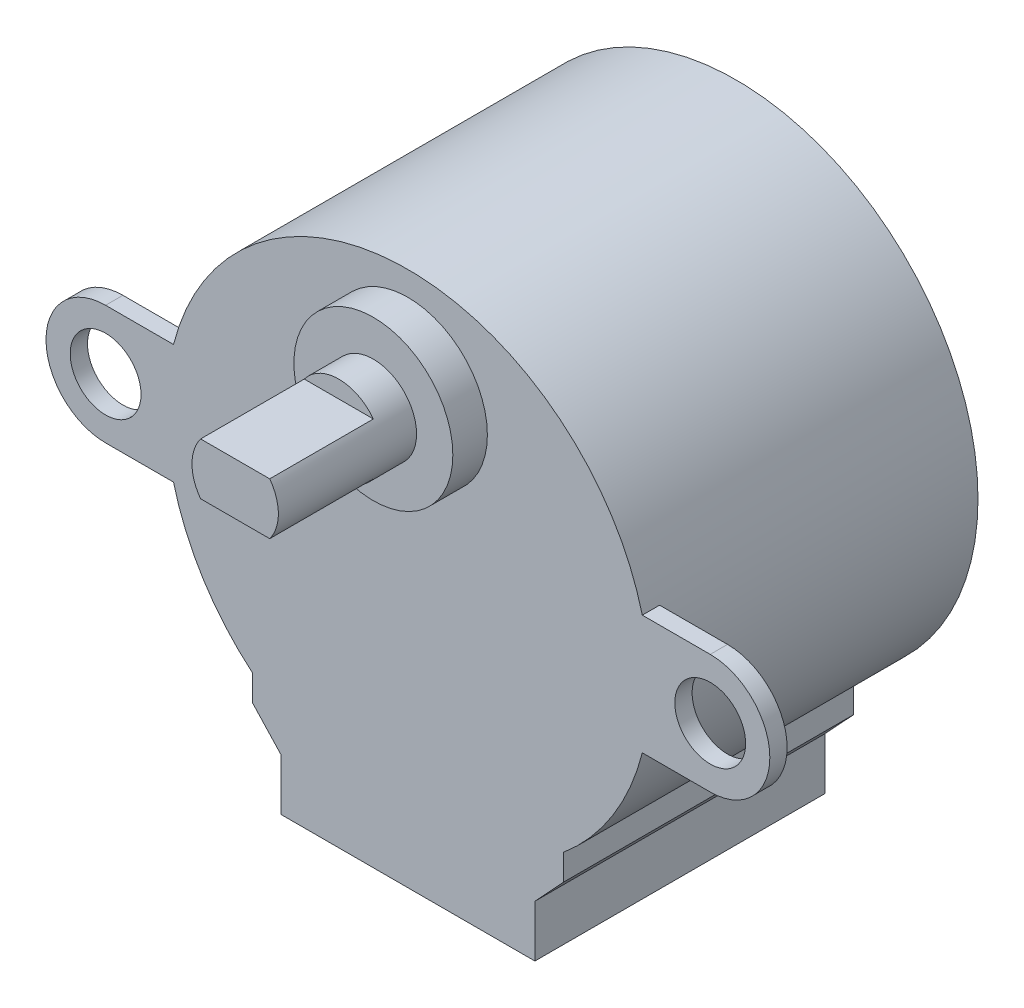
SolidWorks part; units mm, degrees
material "Air"
ref_plane "Front Plane" through (0, 0, 0) normal (0, 0, 1) x (1, 0, 0)
ref_plane "Top Plane" through (0, 0, 0) normal (0, 1, 0) x (1, 0, 0)
ref_plane "Right Plane" through (0, 0, 0) normal (1, 0, 0) x (0, 0, -1)
sketch "Sketch1" plane through (0, 0, 0) normal (0, 0, 1) x (1, 0, 0)
  circle A0 centre (0, 0) radius 14
  dimension "D1" = 28
extrude "Boss-Extrude1" add sketch "Sketch1" along normal blind 19
sketch "Sketch3" plane through (0, 0, 19) normal (0, 0, 1) x (1, 0, 0)
  line L0 (672.6511, 1264.4521) -> (697.6511, 1264.4521) construction
  line L1 (-576.9945, 40.9982) -> (-576.9945, 65.9982) construction
  dimension "D1" = 25
  dimension "D2" = 25
sketch "Sketch2" plane through (0, 0, 19) normal (0, 0, 1) x (1, 0, 0)
  line L0 (-7.35, -17) -> (7.35, -17)
  line L1 (7.35, -17) -> (7.35, -14)
  line L2 (7.35, -14) -> (9, -12.2238)
  line L3 (9, -12.2238) -> (9, -10.7238)
  line L4 (-7.35, -17) -> (-7.35, -14)
  line L5 (-7.35, -14) -> (-9, -12.2238)
  line L6 (-9, -12.2238) -> (-9, -10.7238)
  line L7 (9, -10.7238) -> (-9, -10.7238) construction
  circle A0 centre (0, 0) radius 14 construction
  arc A1 (-9, -10.7238) -> (9, -10.7238) centre (0, 0) ccw
  point P2 (0, -17)
  dimension "D1" = 14.7
  dimension "D2" = 17
  dimension "D3" = 18
  dimension "D4" = 3
  dimension "D5" = 3
  dimension "D6" = 1.5
  dimension "D7" = 1.5
extrude "Boss-Extrude2" add sketch "Sketch2" against normal blind 16.8 contours L1 L2 L3 A1 L6 L5 L4 L0
sketch "Sketch4" plane through (0, -17, 0) normal (0, -1, 0) x (1, 0, 0)
  line L0 (-3, 17.25) -> (3, 17.25) construction
  line L1 (-3, 17.75) -> (3, 17.75)
  line L2 (-3, 16.75) -> (3, 16.75)
  line L3 (-7.35, 19) -> (7.35, 19) construction
  arc A0 (-3, 17.75) -> (-3, 16.75) centre (-3, 17.25) ccw
  arc A1 (3, 16.75) -> (3, 17.75) centre (3, 17.25) ccw
  point P2 (0, 17.25)
  dimension "D1" = 6
  dimension "D2" = 0.5
  dimension "D3" = 1.75
extrude "Cut-Extrude1" cut sketch "Sketch4" against normal blind 2
sketch "Sketch5" plane through (0, 0, 19) normal (0, 0, 1) x (1, 0, 0)
  line L0 (0, 14) -> (0, -18.7354) construction
  line L1 (0, 0) -> (9.5563, 0) construction
  line L2 (-17.5, 3.45) -> (-13.5683, 3.45)
  line L3 (-17.5, -3.45) -> (-13.5683, -3.45)
  line L4 (17.5, -3.45) -> (13.5683, -3.45)
  line L5 (17.5, 3.45) -> (13.5683, 3.45)
  circle A0 centre (-17.5, 0) radius 2.05
  arc A3 (-17.5, 3.45) -> (-17.5, -3.45) centre (-17.5, 0) ccw
  arc A4 (9, -10.7238) -> (-9, -10.7238) centre (0, 0) ccw construction
  arc A5 (13.5683, 3.45) -> (13.5683, -3.45) centre (0, 0) cw
  arc A6 (-13.5683, 3.45) -> (-13.5683, -3.45) centre (0, 0) ccw
  arc A7 (17.5, 3.45) -> (17.5, -3.45) centre (17.5, 0) cw
  circle A8 centre (17.5, 0) radius 2.05
  dimension "D1" = 4.1
  dimension "D3" = 6.9
extrude "Boss-Extrude3" add sketch "Sketch5" against normal blind 1
sketch "Sketch6" plane through (0, 0, 19) normal (0, 0, 1) x (1, 0, 0)
  line L0 (-24.9917, 0) -> (30.299, 0) construction
  line L1 (0, 14.8773) -> (0, -18.0753) construction
  circle A0 centre (0, 8) radius 4.6
  dimension "D1" = 9.2
  dimension "D2" = 8
extrude "Boss-Extrude4" add sketch "Sketch6" along normal blind 2
sketch "Sketch7" plane through (0, 0, 21) normal (0, 0, 1) x (1, 0, 0)
  circle A0 centre (0, 8) radius 2.5
  dimension "D1" = 5
extrude "Boss-Extrude5" add sketch "Sketch7" along normal blind 8
sketch "Sketch8" plane through (0, 0, 29) normal (0, 0, 1) x (1, 0, 0)
  line L0 (-2, 9.5) -> (2, 9.5)
  line L1 (-2, 6.5) -> (2, 6.5)
  line L2 (0, 9.5) -> (0, 6.5) construction
  circle A0 centre (0, 8) radius 2.5
  point P9 (0, 8)
  circle M4 centre (0, 8) radius 2.5
  dimension "D2" = 5
  dimension "D1" = 3
extrude "Cut-Extrude2" cut sketch "Sketch8" against normal blind 6 contours L0 M4 | L1 M4
sketch "Sketch9" plane through (0, 0, 19) normal (0, 0, 1) x (1, 0, 0)
  line L11 (13.5683, -3.45) -> (17.5, -3.45)
  line L12 (17.5, 3.45) -> (13.5683, 3.45)
  line L13 (-13.5683, 3.45) -> (-17.5, 3.45)
  line L14 (-17.5, -3.45) -> (-13.5683, -3.45)
  line L15 (-9, -10.7238) -> (-9, -12.2238)
  line L16 (-9, -12.2238) -> (-7.35, -14)
  line L17 (-7.35, -14) -> (-7.35, -17)
  line L18 (-7.35, -17) -> (7.35, -17)
  line L19 (7.35, -17) -> (7.35, -14)
  line L20 (7.35, -14) -> (9, -12.2238)
  line L21 (9, -12.2238) -> (9, -10.7238)
  line L22 (13.5683, -3.45) -> (17.5, -3.45)
  line L23 (17.5, 3.45) -> (13.5683, 3.45)
  line L24 (-13.5683, 3.45) -> (-17.5, 3.45)
  line L25 (-17.5, -3.45) -> (-13.5683, -3.45)
  line L26 (-9, -10.7238) -> (-9, -12.2238)
  line L27 (-9, -12.2238) -> (-7.35, -14)
  line L28 (-7.35, -14) -> (-7.35, -17)
  line L29 (-7.35, -17) -> (7.35, -17)
  line L30 (7.35, -17) -> (7.35, -14)
  line L31 (7.35, -14) -> (9, -12.2238)
  line L32 (9, -12.2238) -> (9, -10.7238)
  arc A5 (9, -10.7238) -> (13.5683, -3.45) centre (0, 0) ccw
  arc A6 (17.5, -3.45) -> (17.5, 3.45) centre (17.5, 0) ccw
  arc A7 (13.5683, 3.45) -> (-13.5683, 3.45) centre (0, 0) ccw
  arc A8 (-17.5, 3.45) -> (-17.5, -3.45) centre (-17.5, 0) ccw
  arc A9 (-13.5683, -3.45) -> (-9, -10.7238) centre (0, 0) ccw
  arc A10 (9, -10.7238) -> (13.5683, -3.45) centre (0, 0) ccw
  arc A11 (17.5, -3.45) -> (17.5, 3.45) centre (17.5, 0) ccw
  arc A12 (13.5683, 3.45) -> (-13.5683, 3.45) centre (0, 0) ccw
  arc A13 (-17.5, 3.45) -> (-17.5, -3.45) centre (-17.5, 0) ccw
  arc A14 (-13.5683, -3.45) -> (-9, -10.7238) centre (0, 0) ccw
  dimension "D1" = 0
